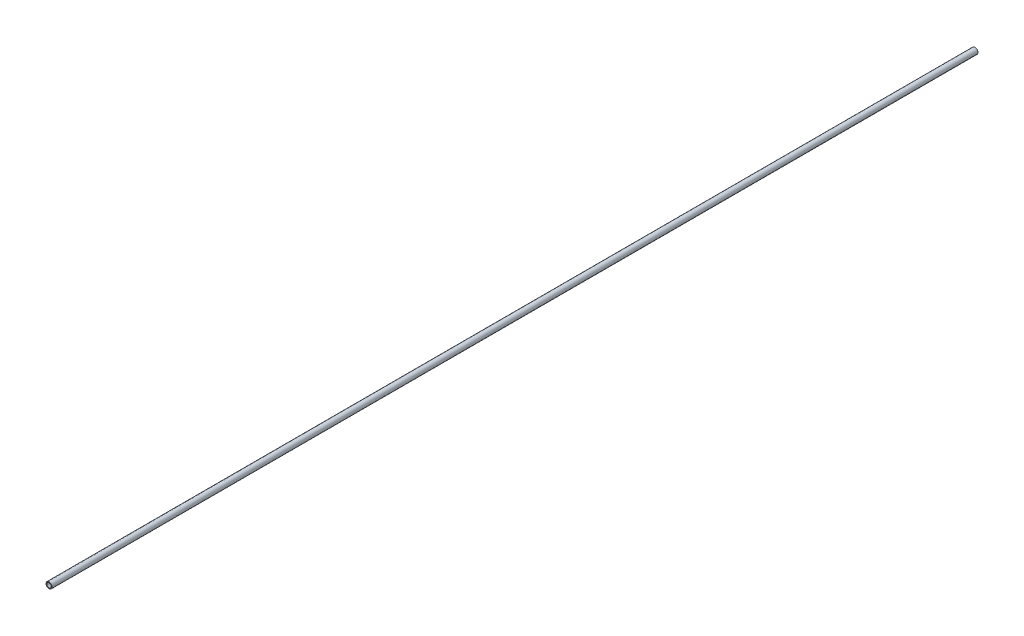
SolidWorks part; units mm, degrees
material "Thornel Mat VMA"
ref_plane "前视基准面" through (0, 0, 0) normal (0, 0, 1) x (1, 0, 0)
ref_plane "上视基准面" through (0, 0, 0) normal (0, 1, 0) x (1, 0, 0)
ref_plane "右视基准面" through (0, 0, 0) normal (1, 0, 0) x (0, 0, -1)
other "Configuration Table"
sketch "草图1" plane through (0, 0, 0) normal (0, 0, 1) x (1, 0, 0)
  circle A0 centre (0, 0) radius 4
  circle A1 centre (0, 0) radius 3
  dimension "D1" = 8
  dimension "D2" = 6
extrude "凸台-拉伸1" add sketch "草图1" along normal blind 1233
